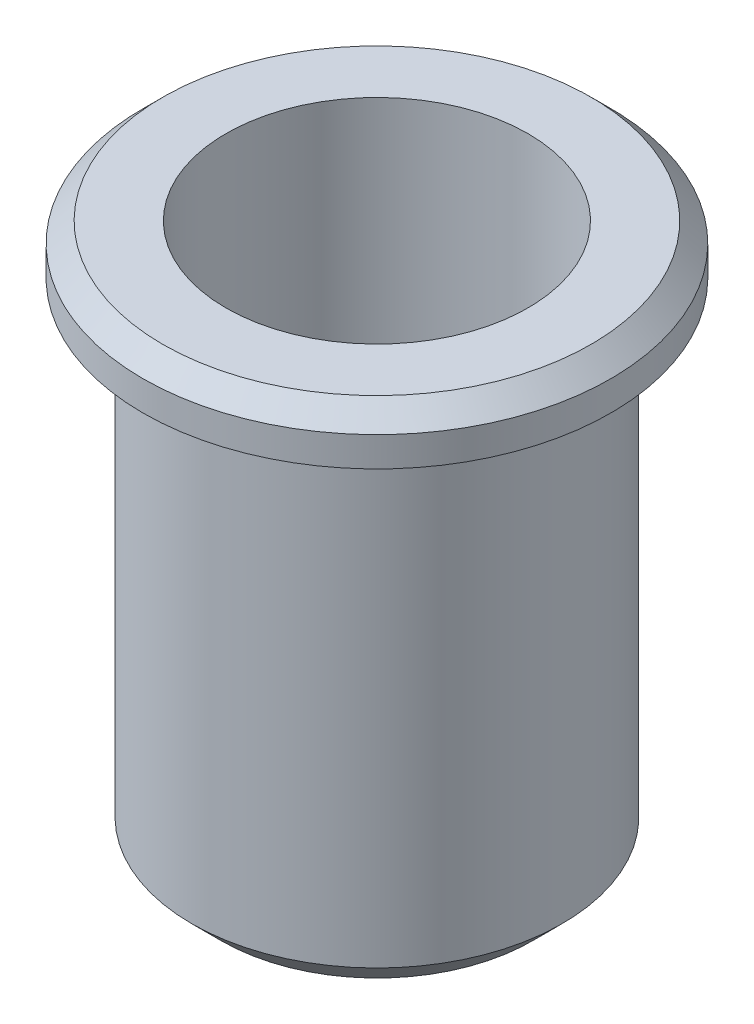
SolidWorks part; units mm, degrees
ref_plane "Front Plane" through (0, 0, 0) normal (0, 0, 1) x (1, 0, 0)
ref_plane "Top Plane" through (0, 0, 0) normal (0, 1, 0) x (1, 0, 0)
ref_plane "Right Plane" through (0, 0, 0) normal (1, 0, 0) x (0, 0, -1)
sketch "Sketch1" plane through (0, 0, 0) normal (0, 0, 1) x (1, 0, 0)
  line L0 (0, 25.1479) -> (0, 0) construction
  line L2 (1.9939, 0) -> (3.988, 0)
  line L3 (3.988, 0) -> (4.75, 0.762)
  line L4 (4.75, 0.762) -> (4.75, 12.73)
  line L5 (4.75, 12.73) -> (6, 12.73)
  line L6 (6, 12.73) -> (6, 13.492)
  line L7 (6, 13.492) -> (5.492, 14)
  line L8 (5.492, 14) -> (3.8735, 14)
  line L9 (3.8735, 14) -> (3.8735, 2.3652)
  line L10 (3.8735, 2.3652) -> (1.9939, 2.3652)
  line L11 (1.9939, 2.3652) -> (1.9939, 0)
  point P3 (1.9295, 0)
  point P4 (6.25, 13.5414)
  point P14 (0.8069, 0)
  dimension "D1" = 14
  dimension "D2" = 9.5
  dimension "D3" = 45
  dimension "D4" = 0.762
  dimension "D5" = 3.9878
  dimension "D6" = 1.27
  dimension "D7" = 12
  dimension "D8" = 7.747
  dimension "D9" = 45
  dimension "D10" = 0.508
revolve "Revolve1" add sketch "Sketch1" angle 360 about L0
